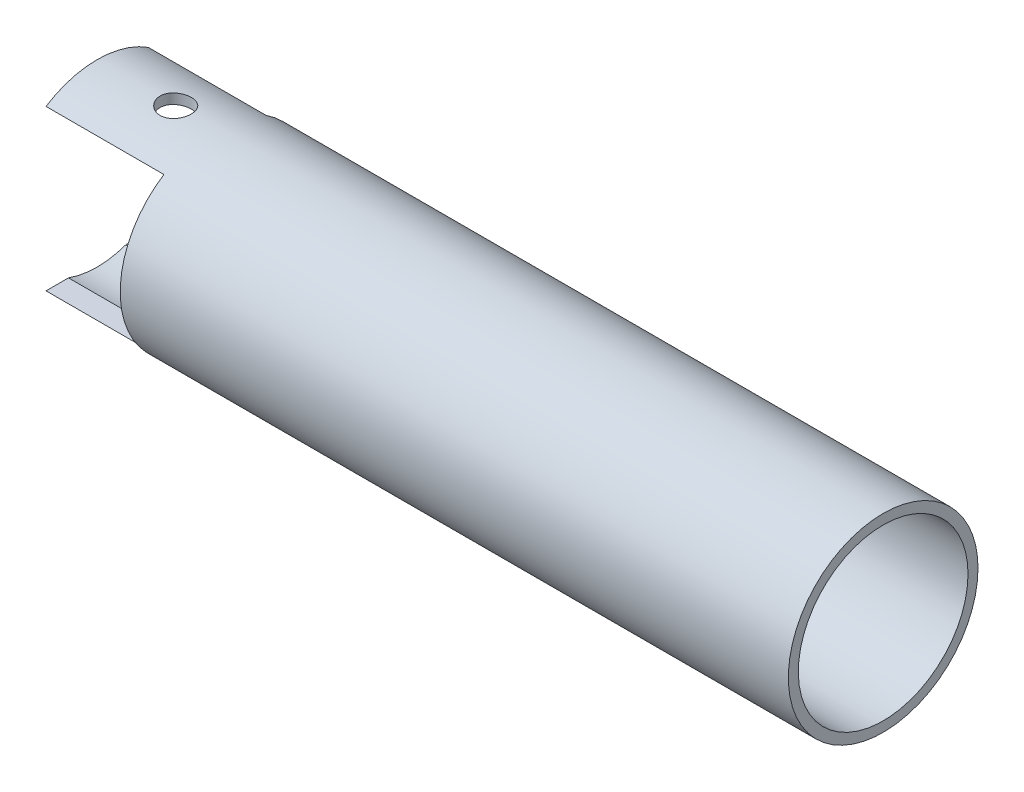
SolidWorks part; units mm, degrees
ref_plane "Front Plane" through (0, 0, 0) normal (0, 0, 1) x (1, 0, 0)
ref_plane "Top Plane" through (0, 0, 0) normal (0, 1, 0) x (1, 0, 0)
ref_plane "Right Plane" through (0, 0, 0) normal (1, 0, 0) x (0, 0, -1)
sketch "Sketch1" plane through (0, 0, 0) normal (1, 0, 0) x (0, 0, -1)
  circle A0 centre (0, 0) radius 1.0795
  circle A1 centre (0, 0) radius 1.2065
  dimension "D1" = 2.413
  dimension "D2" = 2.159
extrude "Boss-Extrude1" add sketch "Sketch1" along normal blind 10
sketch "Sketch2" plane through (0, 0, 0) normal (-1, 0, 0) x (0, 0, 1)
  line L0 (-1.2065, 0) -> (1.2065, 0) construction
  line L1 (-2.1976, -1.016) -> (2.4512, -1.016)
  line L2 (-2.1976, -1.016) -> (-2.1976, 1.016)
  line L3 (-2.1976, 1.016) -> (2.4512, 1.016)
  line L4 (2.4512, -1.016) -> (2.4512, 1.016)
  line L5 (-2.1976, 0) -> (2.4512, 0) construction
  circle A0 centre (0, 0) radius 1.2065 construction
  dimension "D1" = 2.032
extrude "Cut-Extrude1" cut sketch "Sketch2" against normal blind 1.5
sketch "Sketch4" plane through (0, 0, 0) normal (0, 1, 0) x (1, 0, 0)
  line L0 (0, 0.6507) -> (0, 0.3648) construction
  line L1 (0, 0.6507) -> (0, 0.3648) construction
  line L2 (0, 0) -> (1, 0) construction
  line L3 (1.5, 1.2065) -> (1.5, 0.6507) construction
  circle A0 centre (1, 0) radius 0.1984
  dimension "D1" = 0.3969
  dimension "D2" = 0.5
extrude "Cut-Extrude2" cut sketch "Sketch4" against normal blind 5 and the other way blind 5
equation "\"pin_hole_position\"=0.5"
equation "\"D2@Sketch4\"=\"pin_hole_position\""
